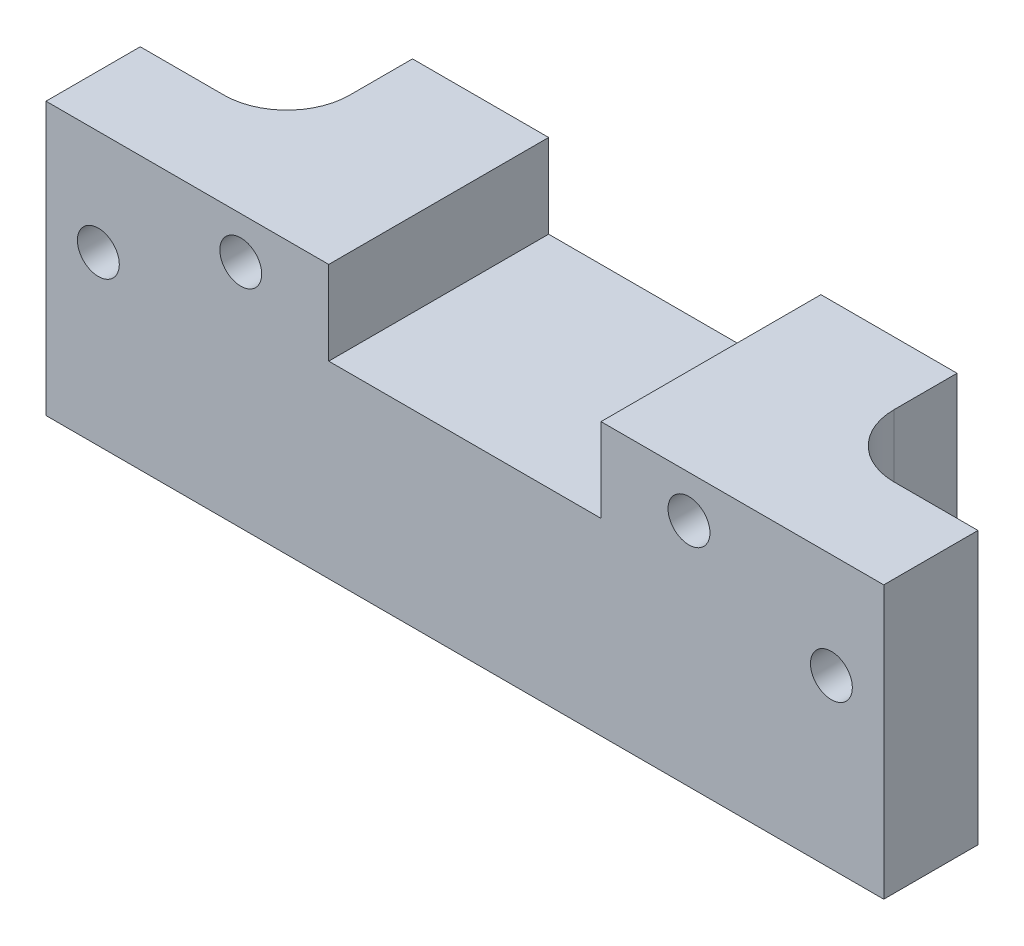
SolidWorks part; units mm, degrees
ref_plane "前视基准面" through (0, 0, 0) normal (0, 0, 1) x (1, 0, 0)
ref_plane "上视基准面" through (0, 0, 0) normal (0, 1, 0) x (1, 0, 0)
ref_plane "右视基准面" through (0, 0, 0) normal (1, 0, 0) x (0, 0, -1)
sketch "草图2" plane through (0, 0, 0) normal (0, 0, 1) x (1, 0, 0)
  line L1 (-20, 6.5) -> (20, 6.5)
  line L2 (-20, 6.5) -> (-20, -6.5)
  line L3 (-20, -6.5) -> (20, -6.5)
  line L4 (20, 6.5) -> (20, -6.5)
  line L5 (-20, 6.5) -> (20, -6.5) construction
  line L6 (-20, -6.5) -> (20, 6.5) construction
  point P0 (0, 0)
  dimension "D1" = 40
  dimension "D2" = 13
extrude "凸台-拉伸1" add sketch "草图2" along normal blind 9.5
sketch "草图3" plane through (0, 0, 0) normal (0, 0, -1) x (-1, 0, 0)
  line L0 (0, 6.5) -> (0, -6.5) construction
  line L1 (-20, 6.5) -> (20, 6.5) construction
  line L2 (20, -6.5) -> (-20, -6.5) construction
  circle A0 centre (-17.5, 1.5) radius 1
  circle A1 centre (17.5, 1.5) radius 1
  dimension "D1" = 2
  dimension "D2" = 17.5
  dimension "D3" = 5
extrude "切除-拉伸1" cut sketch "草图3" against normal blind 10
sketch "草图4" plane through (0, 0, 0) normal (0, 0, -1) x (-1, 0, 0)
  line L0 (0, 6.5) -> (0, -6.5) construction
  line L1 (-20, 6.5) -> (20, 6.5) construction
  line L2 (20, -6.5) -> (-20, -6.5) construction
  line L3 (-6.5, 2.5) -> (-6.5, 6.5)
  line L4 (-6.5, 2.5) -> (6.5, 2.5)
  line L5 (-6.5, 6.5) -> (6.5, 6.5)
  line L6 (6.5, 2.5) -> (6.5, 6.5)
  line L7 (-6.5, 2.5) -> (6.5, 6.5) construction
  line L8 (-6.5, 6.5) -> (6.5, 2.5) construction
  circle A0 centre (-10.7, 4.5) radius 1
  circle A1 centre (10.7, 4.5) radius 1
  point P7 (0, 4.5)
  dimension "D5" = 2
  dimension "D1" = 13
  dimension "D2" = 4
  dimension "D3" = 4
  dimension "D4" = 6.5
  dimension "D6" = 10.7
  dimension "D7" = 2
extrude "切除-拉伸2" cut sketch "草图4" against normal blind 10
sketch "草图5" plane through (0, 0, 0) normal (0, 0, -1) x (-1, 0, 0)
  line L0 (20, -6.5) -> (-20, -6.5) construction
  line L1 (-20, 6.5) -> (-13, 6.5)
  line L2 (-20, 6.5) -> (-20, -6.5)
  line L3 (-20, -6.5) -> (-13, -6.5)
  line L4 (-13, 6.5) -> (-13, -6.5)
  line L6 (20, 6.5) -> (13, 6.5)
  line L7 (20, 6.5) -> (20, -6.5)
  line L8 (20, -6.5) -> (13, -6.5)
  line L9 (13, 6.5) -> (13, -6.5)
  dimension "D1" = 7
  dimension "D2" = 7
extrude "切除-拉伸3" cut sketch "草图5" against normal blind 5
fillet "圆角1" radius 3 2 edges at (-13, 0, 5) (13, 0, 5)
sketch "草图6" plane through (0, 0, 0) normal (0, 0, -1) x (-1, 0, 0)
  line L0 (13, -6.5) -> (-13, -6.5) construction
  line L1 (-13, -2.5) -> (13, -2.5)
  line L8 (-6.5, 6.5) -> (-13, 6.5)
  line L9 (-13, 6.5) -> (-13, -6.5)
  line L10 (-13, -6.5) -> (13, -6.5)
  line L11 (13, -6.5) -> (13, 6.5)
  line L12 (13, 6.5) -> (6.5, 6.5)
  line L13 (6.5, 6.5) -> (6.5, 2.5)
  line L14 (6.5, 2.5) -> (-6.5, 2.5)
  line L15 (-6.5, 2.5) -> (-6.5, 6.5)
  line L16 (-6.5, 6.5) -> (-13, 6.5)
  line L17 (-13, 6.5) -> (-13, -2.5)
  line L19 (13, -2.5) -> (13, 6.5)
  line L20 (13, 6.5) -> (6.5, 6.5)
  line L21 (6.5, 6.5) -> (6.5, 2.5)
  line L22 (6.5, 2.5) -> (-6.5, 2.5)
  line L23 (-6.5, 2.5) -> (-6.5, 6.5)
  circle A0 centre (-10.7, 4.5) radius 1 construction
  circle A1 centre (-10.7, 4.5) radius 1
  circle A2 centre (10.7, 4.5) radius 1 construction
  circle A3 centre (10.7, 4.5) radius 1
  dimension "D2" = 4
  dimension "D1" = 0
extrude "凸台-拉伸2" add sketch "草图6" along normal blind 1
